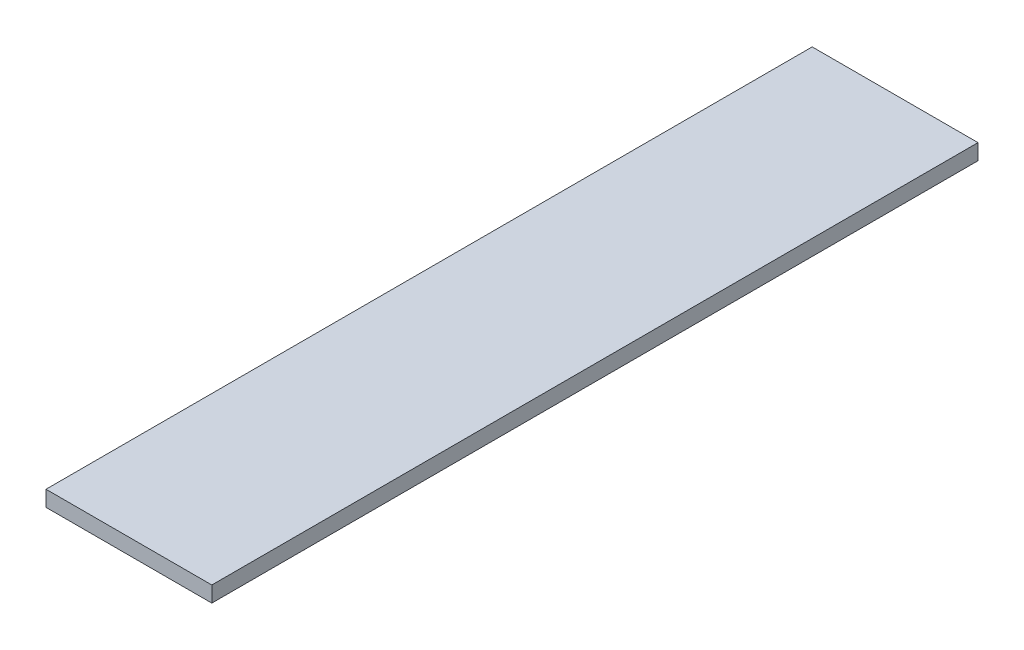
SolidWorks part; units mm, degrees
material "EngineeredWood - Painted"
ref_plane "Front Plane" through (0, 0, 0) normal (0, 0, 1) x (1, 0, 0)
ref_plane "Top Plane" through (0, 0, 0) normal (0, 1, 0) x (1, 0, 0)
ref_plane "Right Plane" through (0, 0, 0) normal (1, 0, 0) x (0, 0, -1)
sketch "Sketch1" plane through (0, 0, 0) normal (0, 0, 1) x (1, 0, 0)
  line L1 (0, 0) -> (184.15, 0)
  line L2 (0, 0) -> (0, 17.4498)
  line L3 (0, 17.4498) -> (184.15, 17.4498)
  line L4 (184.15, 0) -> (184.15, 17.4498)
  dimension "D1" = 184.15
  dimension "D2" = 17.4498
extrude "Boss-Extrude1" add sketch "Sketch1" along normal blind 850.9
